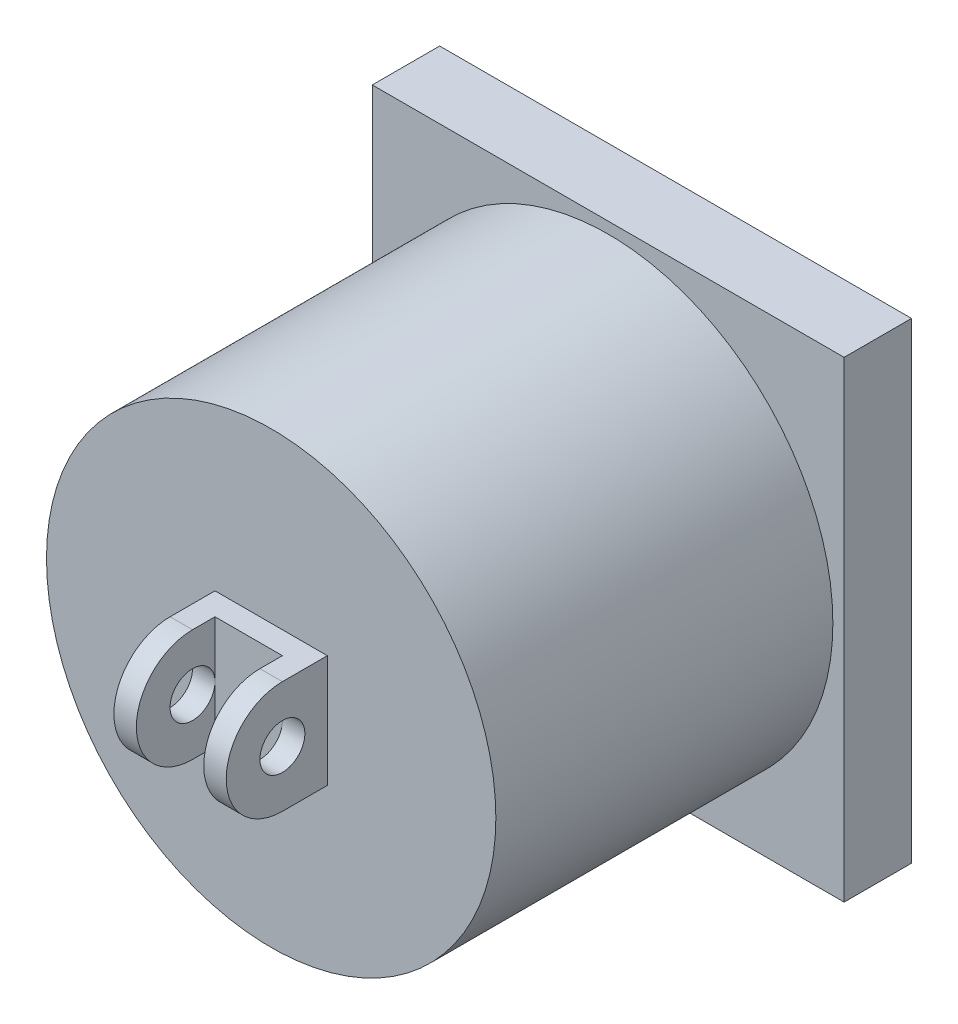
SolidWorks part; units mm, degrees
ref_plane "Front Plane" through (0, 0, 0) normal (0, 0, 1) x (1, 0, 0)
ref_plane "Top Plane" through (0, 0, 0) normal (0, 1, 0) x (1, 0, 0)
ref_plane "Right Plane" through (0, 0, 0) normal (1, 0, 0) x (0, 0, -1)
sketch "Sketch1" plane through (0, 0, 0) normal (0, 0, 1) x (1, 0, 0)
  circle A0 centre (0, 0) radius 10
  dimension "D1" = 20
extrude "Boss-Extrude1" add sketch "Sketch1" along normal blind 15
sketch "Sketch2" plane through (0, 0, 0) normal (0, 0, -1) x (-1, 0, 0)
  line L1 (10.5, -10.5) -> (-10.5, -10.5)
  line L2 (10.5, -10.5) -> (10.5, 10.5)
  line L3 (10.5, 10.5) -> (-10.5, 10.5)
  line L4 (-10.5, -10.5) -> (-10.5, 10.5)
  line L5 (10.5, -10.5) -> (-10.5, 10.5) construction
  line L6 (10.5, 10.5) -> (-10.5, -10.5) construction
  point P0 (0, 0)
  dimension "D1" = 21
extrude "Boss-Extrude2" add sketch "Sketch2" along normal blind 3
sketch "Sketch3" plane through (0, 0, 0) normal (1, 0, 0) x (0, 0, -1)
  line L0 (0, 0) -> (-15, 0) construction
  line L1 (-15, 10) -> (-15, -10) construction
  line L2 (-15, 2.5) -> (-15, -2.5)
  line L3 (-15, 2.5) -> (-17, 2.5)
  line L4 (-15, -2.5) -> (-17, -2.5)
  arc A0 (-17, 2.5) -> (-17, -2.5) centre (-17, 0) ccw
  circle A1 centre (-17, 0) radius 1
  point P7 (-15, 0)
  dimension "D3" = 2
  dimension "D1" = 5
  dimension "D2" = 2
extrude "Boss-Extrude3" add sketch "Sketch3" along normal mid plane 5
ref_plane "Plane1" through (0, 0, 19.5) normal (0, 0, 1) x (1, 0, 0)
sketch "Sketch4" plane through (0, 0, 19.5) normal (0, 0, 1) x (1, 0, 0)
  line L0 (2.5, 2.5) -> (-2.5, 2.5) construction
  line L1 (-1.5, 2.5) -> (1.5, 2.5)
  line L2 (-1.5, 2.5) -> (-1.5, -2.5)
  line L3 (-1.5, -2.5) -> (1.5, -2.5)
  line L4 (1.5, 2.5) -> (1.5, -2.5)
  line L5 (2.5, -2.5) -> (-2.5, -2.5) construction
  line L6 (-2.5, -2.5) -> (-2.5, 2.5) construction
  line L7 (2.5, -2.5) -> (2.5, 2.5) construction
  dimension "D1" = 1
  dimension "D2" = 1
extrude "Cut-Extrude1" cut sketch "Sketch4" against normal blind 3.5
